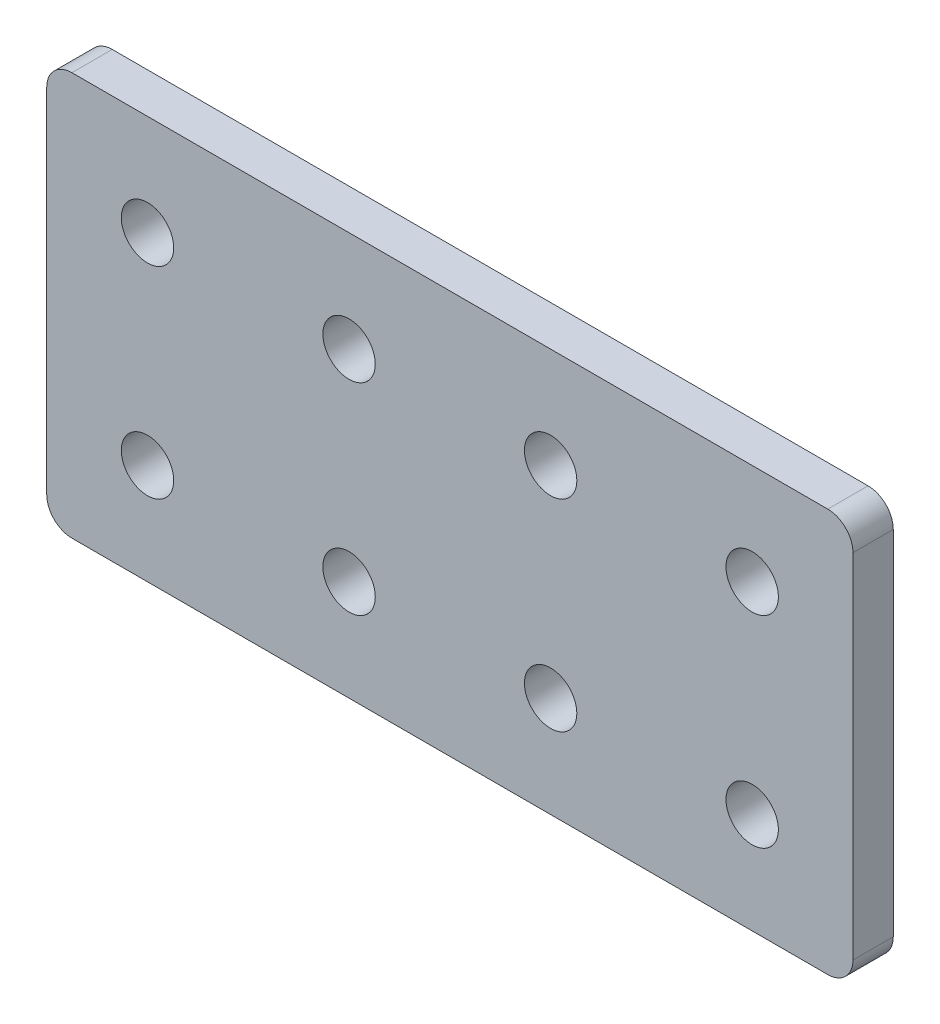
SolidWorks part; units mm, degrees
ref_plane "Спереди" through (0, 0, 0) normal (0, 0, 1) x (1, 0, 0)
ref_plane "Сверху" through (0, 0, 0) normal (0, 1, 0) x (1, 0, 0)
ref_plane "Справа" through (0, 0, 0) normal (1, 0, 0) x (0, 0, -1)
sketch "Эскиз1" plane through (0, 0, 0) normal (0, 0, 1) x (1, 0, 0)
  line L1 (2.5, 0) -> (77.5, 0)
  line L2 (0, -2.5) -> (0, -37.5)
  line L4 (80, -2.5) -> (80, -37.5)
  line L7 (10, -10) -> (30, -10) construction
  line L8 (10, -10) -> (10, -30) construction
  line L11 (77.5, -40) -> (2.5, -40)
  circle A5 centre (10, -10) radius 2.6
  arc A17 (2.5, 0) -> (0, -2.5) centre (2.5, -2.5) ccw
  arc A18 (80, -2.5) -> (77.5, 0) centre (77.5, -2.5) ccw
  circle A24 centre (30, -10) radius 2.6
  circle A25 centre (50, -10) radius 2.6
  circle A26 centre (70, -10) radius 2.6
  circle A27 centre (30, -30) radius 2.6
  circle A28 centre (50, -30) radius 2.6
  circle A29 centre (70, -30) radius 2.6
  circle A30 centre (10, -30) radius 2.6
  arc A34 (80, -37.5) -> (77.5, -40) centre (77.5, -37.5) cw
  arc A35 (2.5, -40) -> (0, -37.5) centre (2.5, -37.5) cw
  point P10 (0, 0)
  point P15 (80, -40)
  point P22 (80, 0)
  point P25 (80, -40)
  dimension "D3" = 80
  dimension "D4" = 2.5
  dimension "D6" = 40
  dimension "D7" = 2.5
  dimension "D8" = 5.2
  dimension "D10" = 10
  dimension "D11" = 2.5
  dimension "D9" = 10
  dimension "D19" = 20
  dimension "D20" = 20
  dimension "D17" = 4
  dimension "D18" = 2
extrude "Бобышка-Вытянуть1" add sketch "Эскиз1" along normal blind 4
